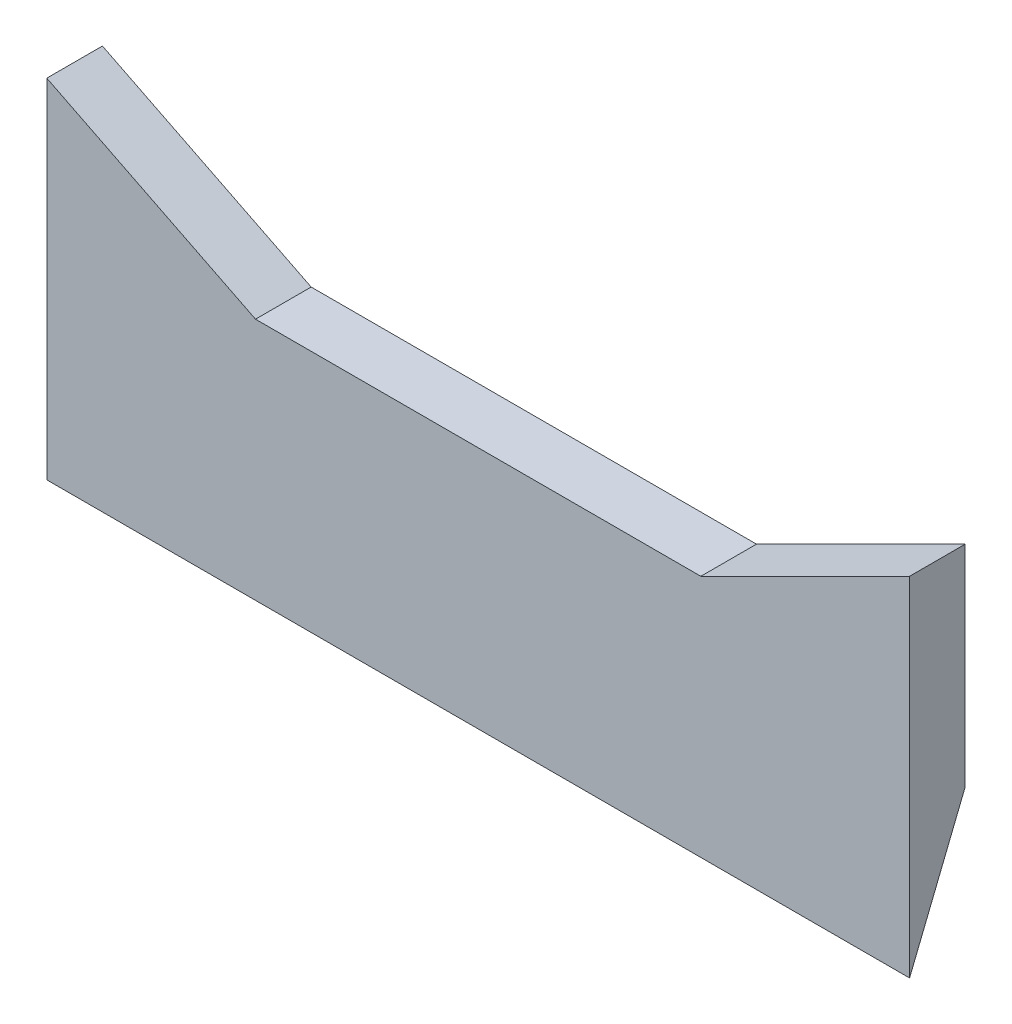
SolidWorks part; units mm, degrees
material "AISI 4340 Aço, normalizado"
ref_plane "Plano frontal" through (0, 0, 0) normal (0, 0, 1) x (1, 0, 0)
ref_plane "Plano superior" through (0, 0, 0) normal (0, 1, 0) x (1, 0, 0)
ref_plane "Plano direito" through (0, 0, 0) normal (1, 0, 0) x (0, 0, -1)
sketch "Esboço1" plane through (0, 0, 0) normal (0, 0, 1) x (1, 0, 0)
  line L0 (0, 0) -> (124, 0)
  line L1 (124, 0) -> (124, 50)
  line L2 (124, 50) -> (94, 35)
  line L3 (94, 35) -> (30, 35)
  line L4 (30, 35) -> (0, 50)
  line L5 (0, 50) -> (0, 0)
  dimension "D1" = 124
  dimension "D2" = 50
  dimension "D3" = 30
  dimension "D4" = 30
  dimension "D5" = 35
extrude "Ressalto-extrusão1" add sketch "Esboço1" along normal blind 8
sketch "Esboço2" plane through (0, 0, 0) normal (-1, 0, 0) x (0, 0, 1)
  line L0 (8, 0) -> (0, 0)
  line L1 (0, 0) -> (0, 19.8007)
  line L2 (0, 50) -> (0, 0) construction
  line L3 (8, 0) -> (0, 0) construction
  line L4 (0, 19.8007) -> (8, 0)
  dimension "D1" = 19.8007
  dimension "D3" = 19.8007
  dimension "D4" = 68
extrude "Corte-extrusão1" cut sketch "Esboço2" against normal through all
